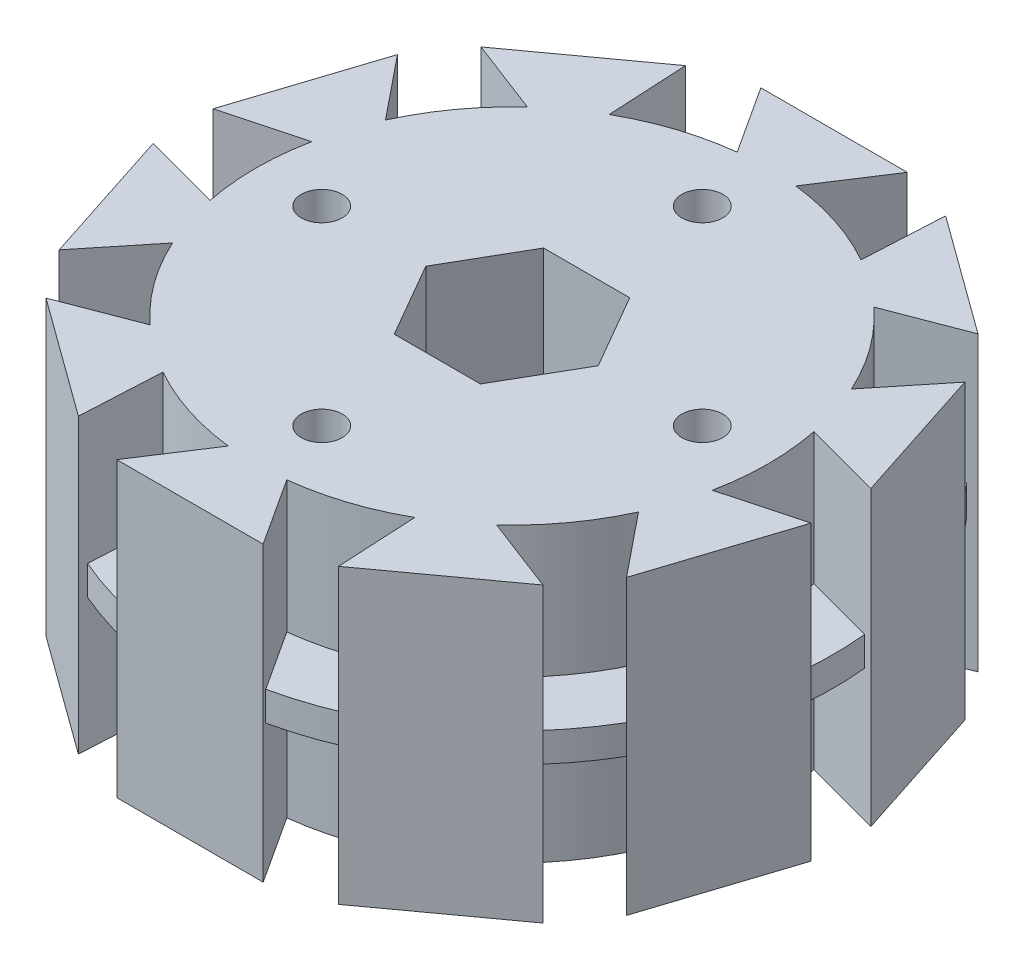
SolidWorks part; units mm, degrees
ref_plane "Front Plane" through (0, 0, 0) normal (0, 0, 1) x (1, 0, 0)
ref_plane "Top Plane" through (0, 0, 0) normal (0, 1, 0) x (1, 0, 0)
ref_plane "Right Plane" through (0, 0, 0) normal (1, 0, 0) x (0, 0, -1)
sketch "Sketch1" plane through (0, 0, 0) normal (0, 1, 0) x (1, 0, 0)
  circle A0 centre (0, 0) radius 22.225
  dimension "D1" = 44.45
extrude "Boss-Extrude1" add sketch "Sketch1" along normal blind 25.4
sketch "Sketch2" plane through (0, 0, 0) normal (0, -1, 0) x (1, 0, 0)
  line L1 (7.479, 0) -> (3.7395, 6.477)
  line L2 (3.7395, 6.477) -> (-3.7395, 6.477)
  line L3 (-3.7395, 6.477) -> (-7.479, 0)
  line L4 (-7.479, 0) -> (-3.7395, -6.477)
  line L5 (-3.7395, -6.477) -> (3.7395, -6.477)
  line L6 (3.7395, -6.477) -> (7.479, 0)
  circle A0 centre (0, 0) radius 6.477 construction
  dimension "D1" = 12.954
extrude "Cut-Extrude1" cut sketch "Sketch2" against normal through all
sketch "Sketch3" plane through (0, 0, 0) normal (0, -1, 0) x (1, 0, 0)
  line L0 (-2.54, 22.0794) -> (-6.35, 27.94)
  line L1 (-6.35, 27.94) -> (6.35, 27.94)
  line L2 (0, 27.94) -> (0, 0) construction
  line L3 (2.54, 22.0794) -> (6.35, 27.94)
  circle A0 centre (0, 0) radius 22.225 construction
  arc A1 (2.54, 22.0794) -> (-2.54, 22.0794) centre (0, 0) ccw
  dimension "D1" = 6.35
  dimension "D2" = 27.94
  dimension "D3" = 2.54
extrude "Boss-Extrude2" add sketch "Sketch3" against normal up to surface (25.4 mm away) up to face at (0, 25.4, 0)
pattern_circular "CirPattern1" count 10 over 360 about axis through (0, 0, 0) along (0, 1, 0) of "Boss-Extrude2"
ref_plane "Plane1" through (0, 12.7, 0) normal (0, 1, 0) x (1, 0, 0)
sketch "Sketch5" plane through (0, 12.7, 0) normal (0, 1, 0) x (1, 0, 0)
  line L0 (6.35, -27.94) -> (-6.35, -27.94) construction
  circle A0 centre (0, 0) radius 27.94
  circle A1 centre (0, 0) radius 22.225
  arc A2 (-10.923, -19.3556) -> (-2.54, -22.0794) centre (0, 0) ccw construction
extrude "Boss-Extrude3" add sketch "Sketch5" along normal mid plane 2.54
sketch "Sketch6" plane through (0, 25.4, 0) normal (0, 1, 0) x (1, 0, 0)
  line L0 (-16.51, 0) -> (16.51, 0) construction
  circle A0 centre (-16.51, 0) radius 1.778
  circle A1 centre (0, 16.51) radius 1.778
  circle A2 centre (16.51, 0) radius 1.778
  circle A3 centre (0, -16.51) radius 1.778
  point P14 (0, 0)
  dimension "D2" = 3.556
  dimension "D1" = 33.02
  dimension "D3" = 4
extrude "Cut-Extrude2" cut sketch "Sketch6" against normal through all
